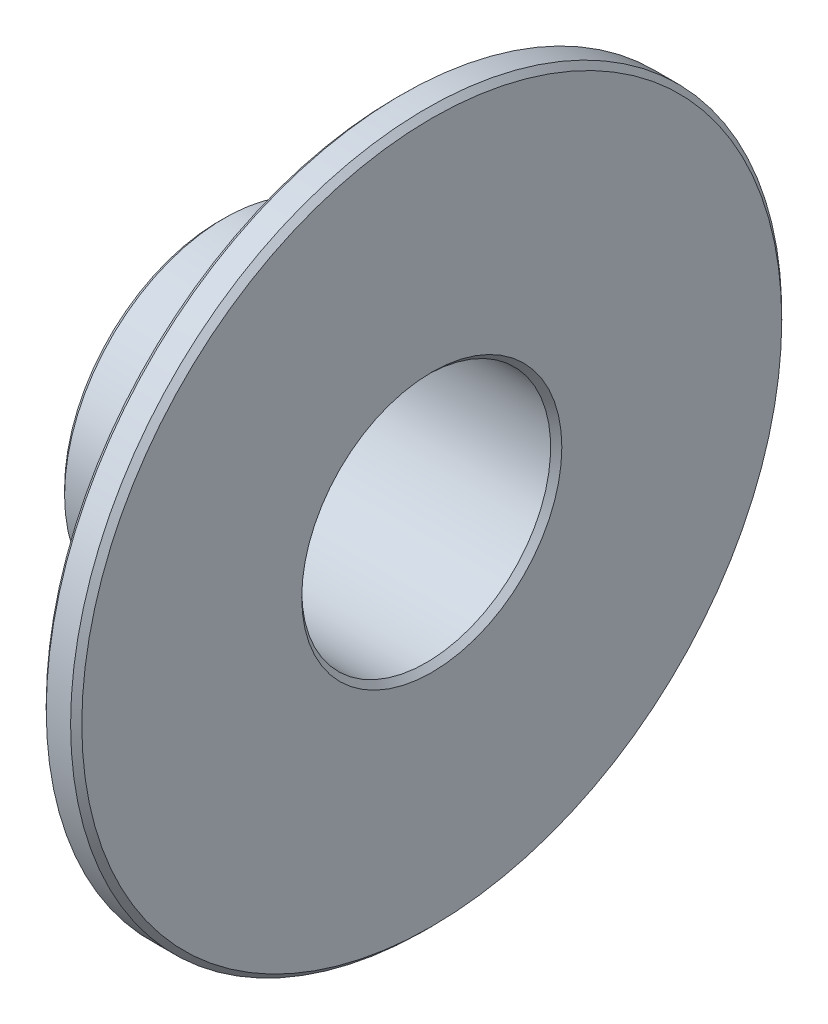
SolidWorks part; units mm, degrees
material "6061-T6 (SS)"
ref_plane "Front Plane" through (0, 0, 0) normal (0, 0, 1) x (1, 0, 0)
ref_plane "Top Plane" through (0, 0, 0) normal (0, 1, 0) x (1, 0, 0)
ref_plane "Right Plane" through (0, 0, 0) normal (1, 0, 0) x (0, 0, -1)
sketch "Sketch1" plane through (0, 0, 0) normal (0, 0, 1) x (1, 0, 0)
  line L0 (0, 0) -> (73.7918, 0) construction
  line L1 (0, 0) -> (-64.2399, 0) construction
  line L2 (-15.825, 13.7875) -> (-15.825, 11.6125)
  line L3 (-15.325, 14.2875) -> (0, 14.2875)
  line L4 (0, 14.2875) -> (0, 31.25)
  line L5 (0.5, 31.75) -> (2.675, 31.75)
  line L6 (3.175, 31.25) -> (3.175, 11.6125)
  line L7 (-15.325, 11.1125) -> (2.675, 11.1125)
  line L8 (0, 23.7294) -> (-10, 23.7294) construction
  line L9 (-10, 23.7294) -> (-13.175, 23.7294) construction
  line L10 (-15.325, 14.2875) -> (-15.825, 13.7875)
  line L11 (-15.825, 11.6125) -> (-15.325, 11.1125)
  line L12 (2.675, 11.1125) -> (3.175, 11.6125)
  line L13 (2.675, 31.75) -> (3.175, 31.25)
  line L14 (0, 31.25) -> (0.5, 31.75)
  point P3 (3.175, 11.1125)
  point P4 (-15.825, 14.2875)
  point P8 (0, 31.75)
  point P9 (3.175, 31.75)
  point P12 (-15.825, 11.1125)
  dimension "D2" = 3.175
  dimension "D3" = 28.575
  dimension "D4" = 22.225
  dimension "D5" = 19
  dimension "D6" = 10
  dimension "D7" = 3.175
revolve "Revolve1" add sketch "Sketch1" angle 360 about L0
